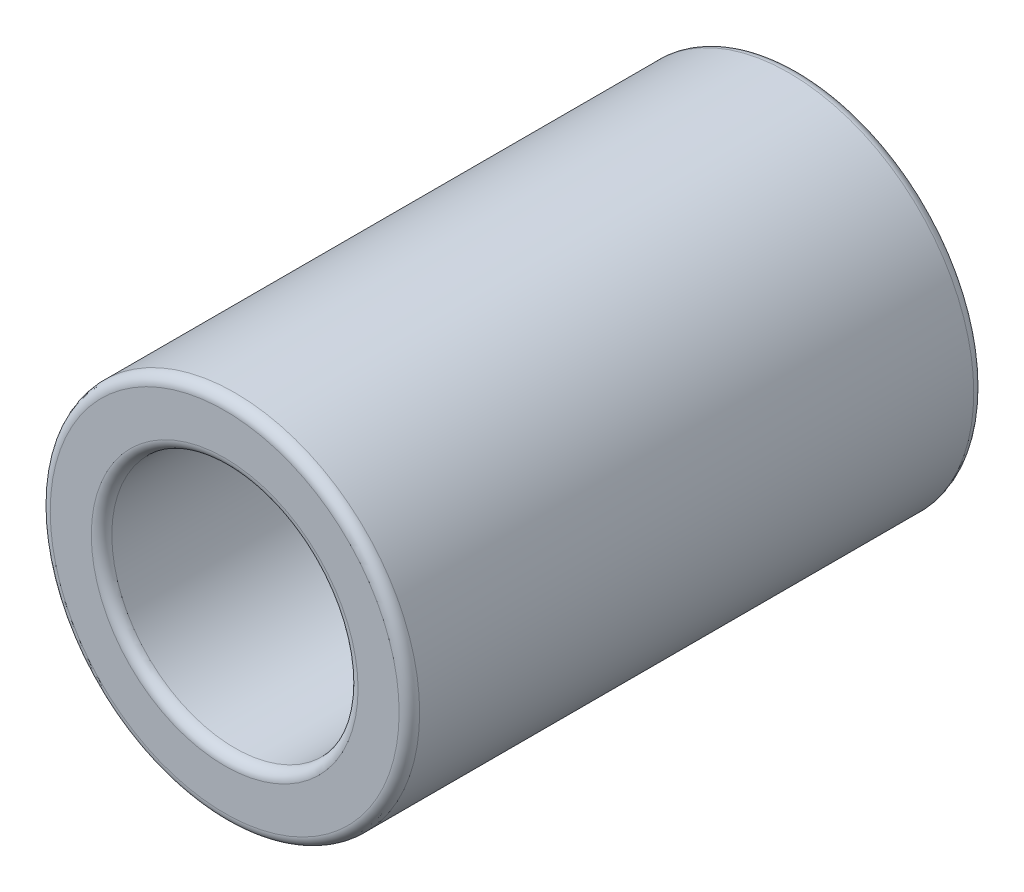
SolidWorks part; units mm, degrees
material "Алюминиевая бронза"
ref_plane "Front" through (0, 0, 0) normal (0, 0, 1) x (1, 0, 0)
ref_plane "Top" through (0, 0, 0) normal (0, 1, 0) x (1, 0, 0)
ref_plane "Right" through (0, 0, 0) normal (1, 0, 0) x (0, 0, -1)
sketch "Эскиз1" plane through (0, 0, 0) normal (0, 0, 1) x (1, 0, 0)
  circle A0 centre (0, 0) radius 18
  circle A1 centre (0, 0) radius 12
  dimension "D1" = 36
  dimension "D2" = 24
extrude "Бобышка-Вытянуть1" add sketch "Эскиз1" along normal mid plane 56
fillet "Скругление1" radius 1 4 edges at (18, 0, -28) (18, 0, 28) (12, 0, -28) (12, 0, 28)
